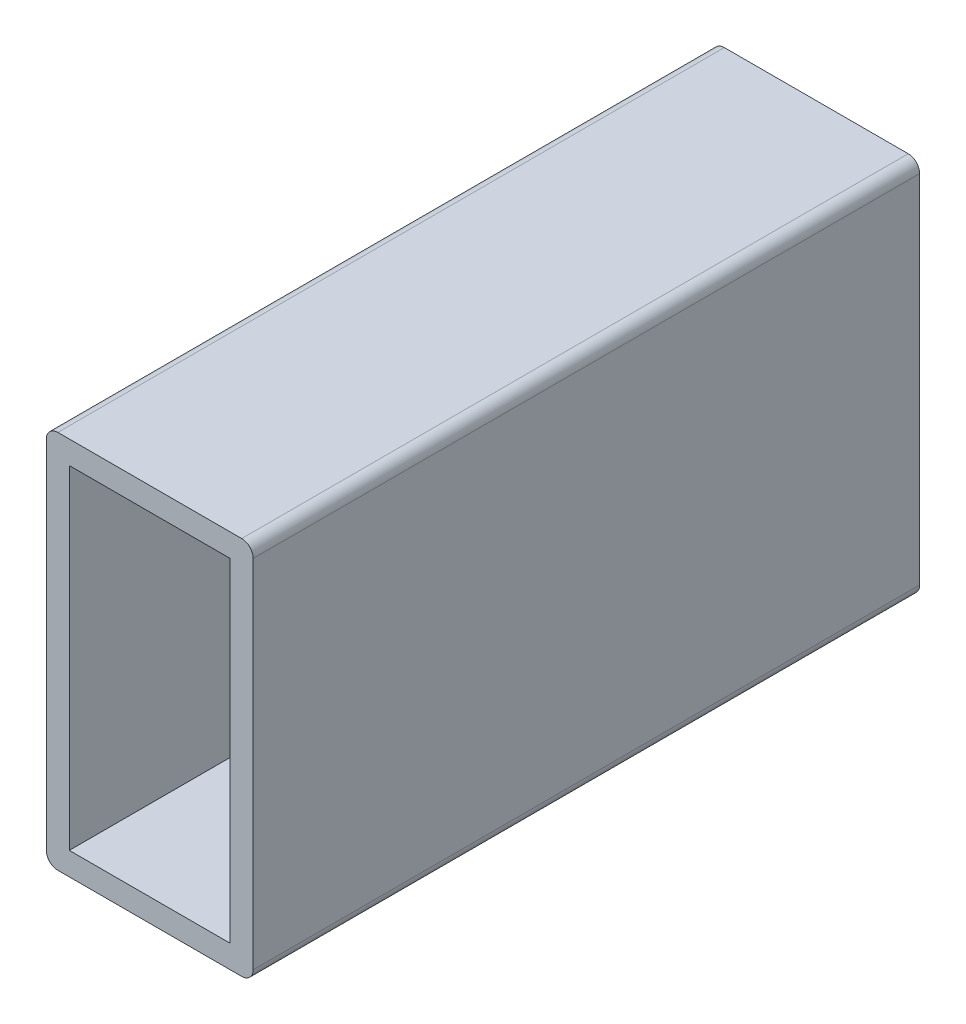
SolidWorks part; units mm, degrees
ref_plane "정면" through (0, 0, 0) normal (0, 0, 1) x (1, 0, 0)
ref_plane "윗면" through (0, 0, 0) normal (0, 1, 0) x (1, 0, 0)
ref_plane "우측면" through (0, 0, 0) normal (1, 0, 0) x (0, 0, -1)
sketch "스케치1" plane through (0, 0, 0) normal (0, 0, 1) x (1, 0, 0)
  line L1 (0, 0) -> (90, 0)
  line L2 (0, 0) -> (0, 165)
  line L3 (0, 165) -> (90, 165)
  line L4 (90, 0) -> (90, 165)
  dimension "D1" = 90
  dimension "D2" = 165
extrude "보스-돌출1" add sketch "스케치1" along normal blind 290
shell "쉘1" thickness 10
fillet "필렛1" radius 5 4 edges at (0, 165, 145) (90, 165, 145) (90, 0, 145) (0, 0, 145)
sketch "스케치2" plane through (0, 0, 0) normal (0, 0, -1) x (-1, 0, 0)
  line L0 (-45, 165) -> (-45, 0) construction
  line L1 (-85, 165) -> (-5, 165) construction
  line L2 (-5, 0) -> (-85, 0) construction
  line L3 (0, 82.5) -> (-90, 82.5) construction
  line L4 (0, 160) -> (0, 5) construction
  line L5 (-90, 5) -> (-90, 160) construction
  circle A0 centre (-45, 82.5) radius 15
  point P14 (-45, 82.5)
  dimension "D1" = 30
extrude "컷-돌출1" cut sketch "스케치2" against normal up to next
